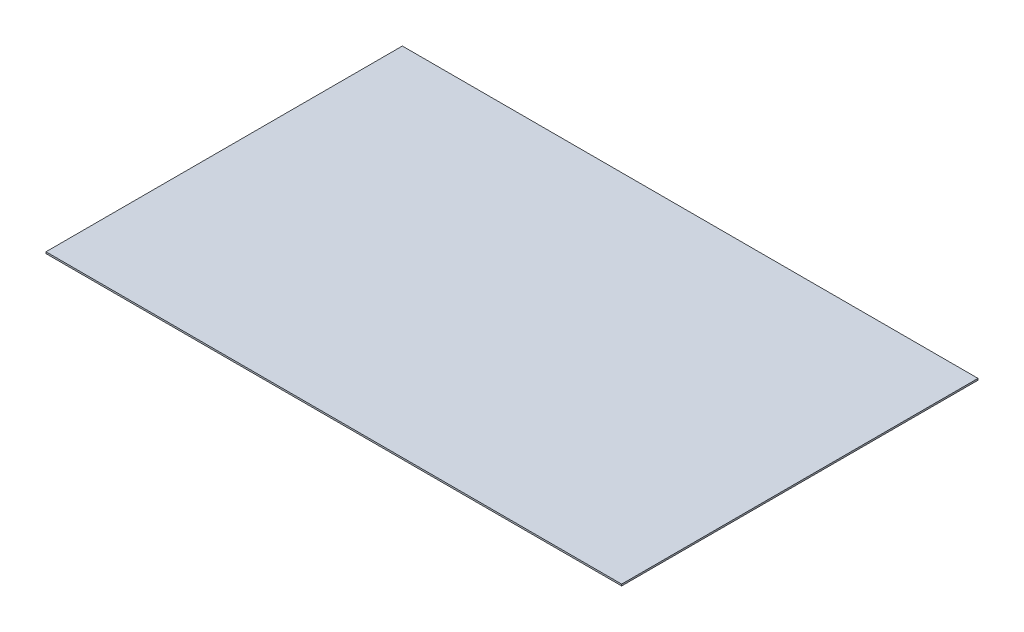
SolidWorks part; units mm, degrees
ref_plane "前视基准面" through (0, 0, 0) normal (0, 0, 1) x (1, 0, 0)
ref_plane "上视基准面" through (0, 0, 0) normal (0, 1, 0) x (1, 0, 0)
ref_plane "右视基准面" through (0, 0, 0) normal (1, 0, 0) x (0, 0, -1)
other "Configuration Table"
sketch "草图1" plane through (0, 0, 0) normal (0, 1, 0) x (1, 0, 0)
  line L1 (-525, 325) -> (525, 325)
  line L2 (-525, 325) -> (-525, -325)
  line L3 (-525, -325) -> (525, -325)
  line L4 (525, 325) -> (525, -325)
  line L5 (0, -325) -> (0, 325) construction
  line L6 (-525, 0) -> (525, 0) construction
  point P0 (0, 0)
  dimension "D1" = 1050
  dimension "D2" = 650
extrude "凸台-拉伸1" add sketch "草图1" along normal blind 3
